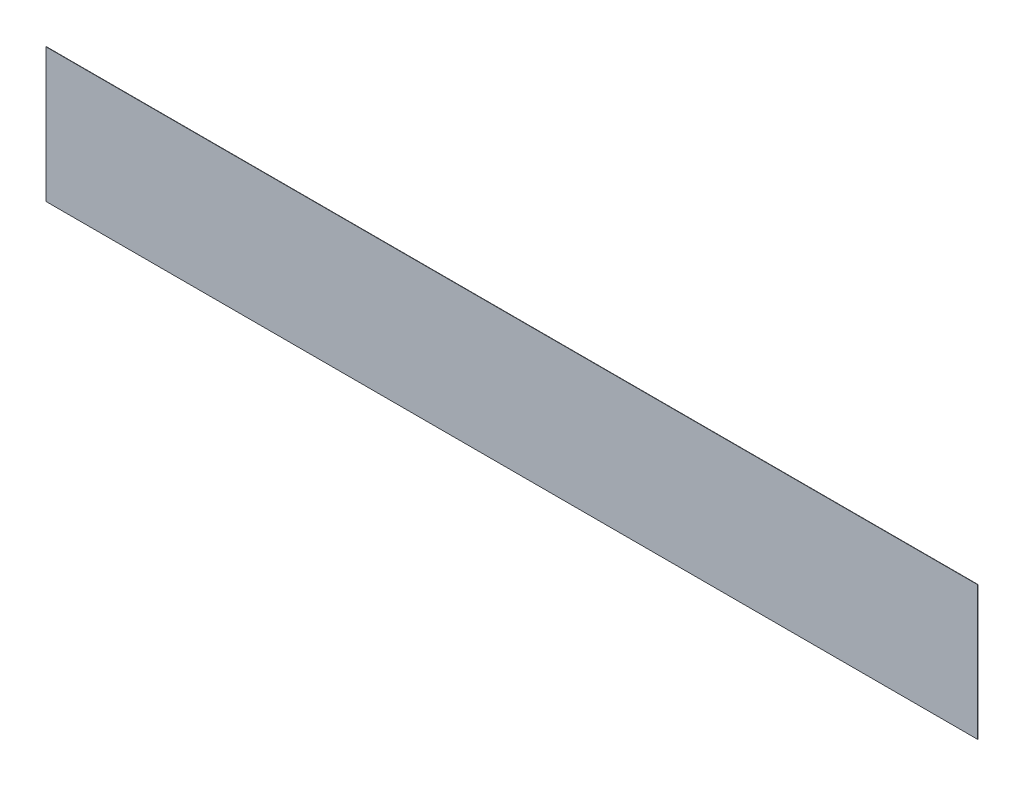
SolidWorks part; units mm, degrees
other "Markup1"
sketch "Sketch4" plane through (-4.5, -9.78, 0.05) normal (0, 0, 1) x (1, 0, 0)
other "Markup2"
sketch "Sketch6" plane through (-4.5, -9.78, 0.05) normal (0, 0, 1) x (1, 0, 0)
ref_plane "Front Plane" through (0, 0, 0) normal (0, 0, 1) x (1, 0, 0)
ref_plane "Top Plane" through (0, 0, 0) normal (0, 1, 0) x (1, 0, 0)
ref_plane "Right Plane" through (0, 0, 0) normal (1, 0, 0) x (0, 0, -1)
sketch "Sketch3" plane through (0, 0, 0) normal (0, 0, 1) x (1, 0, 0)
  line L0 (21.67, 9.78) -> (43.34, 9.78)
  line L1 (0, 9.78) -> (21.67, 9.78)
  line L2 (0, 9.78) -> (0, -9.78)
  line L3 (0, -9.78) -> (21.67, -9.78)
  line L4 (21.67, 9.78) -> (21.67, -9.78)
  line L5 (0, 9.78) -> (21.67, -9.78) construction
  line L6 (0, -9.78) -> (21.67, 9.78) construction
  line L7 (21.67, 9.78) -> (21.67, -9.78)
  line L8 (21.67, -9.78) -> (43.34, -9.78)
  line L9 (43.34, 9.78) -> (43.34, -9.78)
  line L10 (43.34, 9.78) -> (65.01, 9.78)
  line L11 (-4.5, 9.78) -> (0, 9.78)
  line L12 (-4.5, 9.78) -> (-4.5, -9.78)
  line L13 (-4.5, -9.78) -> (0, -9.78)
  line L14 (0, 9.78) -> (0, -9.78)
  line L15 (-4.5, 9.78) -> (0, -9.78) construction
  line L16 (-4.5, -9.78) -> (0, 9.78) construction
  line L17 (43.34, 9.78) -> (43.34, -9.78)
  line L18 (43.34, -9.78) -> (65.01, -9.78)
  line L19 (65.01, 9.78) -> (65.01, -9.78)
  line L20 (65.01, 9.78) -> (86.68, 9.78)
  line L21 (65.01, 9.78) -> (65.01, -9.78)
  line L22 (65.01, -9.78) -> (86.68, -9.78)
  line L23 (86.68, 9.78) -> (86.68, -9.78)
  line L24 (86.68, 9.78) -> (108.35, 9.78)
  line L25 (86.68, 9.78) -> (86.68, -9.78)
  line L26 (86.68, -9.78) -> (108.35, -9.78)
  line L27 (108.35, 9.78) -> (108.35, -9.78)
  line L28 (108.35, 9.78) -> (130.02, 9.78)
  line L29 (108.35, 9.78) -> (108.35, -9.78)
  line L30 (108.35, -9.78) -> (130.02, -9.78)
  line L31 (130.02, 9.78) -> (130.02, -9.78)
  line L32 (-4.5, 0) -> (131.52, 0) construction
  line L33 (130.02, 9.78) -> (131.52, 9.78)
  line L34 (130.02, 9.78) -> (130.02, -9.78)
  line L35 (130.02, -9.78) -> (131.52, -9.78)
  line L36 (131.52, 9.78) -> (131.52, -9.78)
  line L37 (130.02, 9.78) -> (131.52, -9.78) construction
  line L38 (130.02, -9.78) -> (131.52, 9.78) construction
  point P0 (10.835, 0)
  point P9 (0, 0)
  point P10 (0, 0)
  point P11 (43.34, 0)
  point P13 (-2.25, 0)
  point P18 (21.67, 0)
  point P19 (21.67, 0)
  point P24 (43.34, 0)
  point P29 (65.01, 0)
  point P30 (65.01, 0)
  point P35 (86.68, 0)
  point P40 (108.35, 0)
  point P41 (86.68, 0)
  point P42 (108.35, 0)
  point P43 (130.77, 0)
  point P48 (130.02, 0)
  point P49 (130.02, 0)
  dimension "D1" = 21.67
  dimension "D2" = 19.56
  dimension "D3" = 4.5
  dimension "D4" = 1.5
  dimension "D5" = 9.78
extrude "Boss-Extrude1" add sketch "Sketch3" along normal blind 0.05 contours L4 L1 L2 L3 | L9 L0 L4 L8 | L19 L10 L9 L18 | L23 L20 L19 L22 | L27 L24 L23 L26 | L31 L28 L27 L30 | L36 L33 L31 L35 | L12 L13 L14 L11
sketch "Sketch5" plane through (0, 0, 0.05) normal (0, 0, 1) x (1, 0, 0)
  line L0 (0, 9.78) -> (0, -9.78)
  line L1 (-4.5, 9.78) -> (131.52, 9.78) construction
  line L2 (-4.5, -9.78) -> (131.52, -9.78) construction
  line L3 (-4.5, 9.78) -> (-4.5, -9.78) construction
  line L4 (130.02, 9.78) -> (130.02, -9.78)
  line L5 (131.52, 9.78) -> (131.52, -9.78) construction
  line L8 (21.6708, 9.78) -> (21.6708, -9.78)
  line L9 (43.3416, 9.78) -> (43.3416, -9.78)
  line L10 (65.0124, 9.78) -> (65.0124, -9.78)
  line L11 (86.6832, 9.78) -> (86.6832, -9.78)
  line L12 (108.354, 9.78) -> (108.354, -9.78)
  dimension "D1" = 4.5
  dimension "D2" = 1.5
  dimension "D3" = 6
  dimension "D4" = 21.666
ref_plane "Start of RSUs" through (0, 0, 0) normal (1, 0, 0) x (0, -1, 0)
ref_plane "EIC-LAS y midplane" through (0, 0, 0) normal (0, -1, 0) x (1, 0, 0)
ref_plane "End of RSUs" through (130.02, 0, 0) normal (-1, 0, 0) x (0, -1, 0)
ref_plane "EIC-LAS left edge" through (-4.5, 0, 0) normal (1, 0, 0) x (0, -1, 0)
ref_plane "EIC-LAS right edge" through (131.52, 0, 0) normal (-1, 0, 0) x (0, -1, 0)
ref_plane "EIC-LAS top edge" through (0, 9.78, 0) normal (0, -1, 0) x (1, 0, 0)
